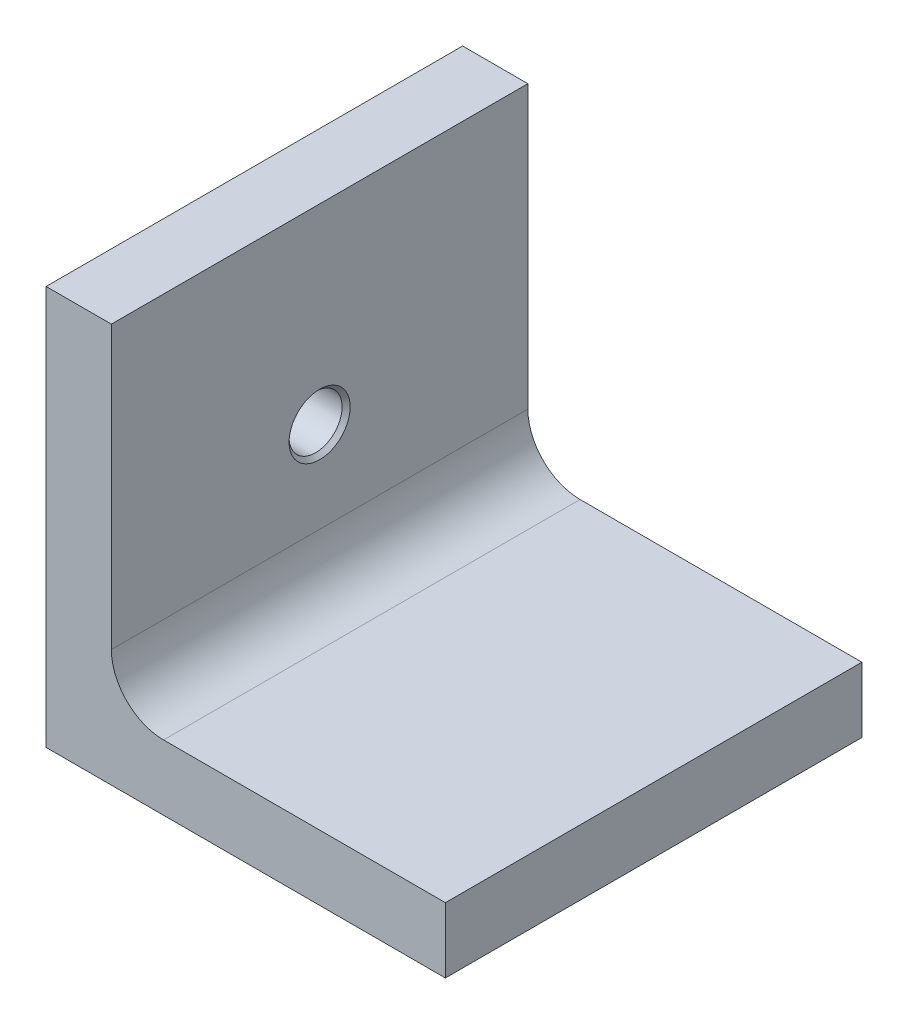
SolidWorks part; units mm, degrees
ref_plane "Front Plane" through (0, 0, 0) normal (0, 0, 1) x (1, 0, 0)
ref_plane "Top Plane" through (0, 0, 0) normal (0, 1, 0) x (1, 0, 0)
ref_plane "Right Plane" through (0, 0, 0) normal (1, 0, 0) x (0, 0, -1)
sketch "Sketch1" plane through (0, 0, 0) normal (0, 0, 1) x (1, 0, 0)
  line L0 (0, 36.5252) -> (0, 0)
  line L1 (0, 0) -> (36.5252, 0)
  line L2 (36.5252, 0) -> (36.5252, 5.969)
  line L3 (36.5252, 5.969) -> (10.7442, 5.969)
  line L4 (5.969, 10.7442) -> (5.969, 36.5252)
  line L5 (5.969, 36.5252) -> (0, 36.5252)
  arc A0 (10.7442, 5.969) -> (5.969, 10.7442) centre (10.7442, 10.7442) cw
  dimension "D5" = 4.7752
  dimension "D1" = 5.969
  dimension "D2" = 5.969
  dimension "D3" = 36.5252
  dimension "D4" = 36.5252
extrude "Boss-Extrude1" add sketch "Sketch1" along normal mid plane 38.1
hole_wizard "#11 (0.191) Diameter Hole1" positions "Sketch10" profile "Sketch9" hole size "#11" standard "Ansi Inch" end condition up to next
sketch "Sketch10" plane through (0, 0, 0) normal (-1, 0, 0) x (0, 0, 1)
  point P0 (0, 19.05)
  dimension "D1" = 19.05
sketch "Sketch9" plane through (0, 19.05, 0) normal (0, 1, 0) x (0, 0, 1)
  line L0 (0, 0) -> (0, 5.969)
  line L1 (0, 5.969) -> (2.794, 5.969)
  line L2 (2.4257, 5.6007) -> (2.4257, 0.3683)
  line L3 (2.4257, 0.3683) -> (2.794, 0)
  line L5 (2.794, 0) -> (0, 0)
  line L6 (-2.4257, 0.3683) -> (-2.794, 0) construction
  line L7 (2.794, 5.969) -> (2.4257, 5.6007)
  line L8 (-2.794, 5.969) -> (-2.4257, 5.6007) construction
  line L11 (0, -6.35) -> (0, 107.95) construction
  dimension "Thru Hole Dia." = 4.8514
  dimension "Thru Hole Depth" = 5.969
  dimension "Near C'Sink Dia." = 5.588
  dimension "Near C'Sink Angle" = 90
  dimension "Far C'Sink Dia." = 5.588
  dimension "Far C'Sink Angle" = 90
hole_wizard "#10-32 Tapped Hole1" positions "Sketch4" profile "Sketch3" tap size "#10-32" standard "Ansi Inch"
sketch "Sketch4" plane through (0, 0, 0) normal (-1, 0, 0) x (0, 0, 1)
  point P0 (0, 19.05)
  dimension "D1" = 19.05
sketch "Sketch3" plane through (0, 19.05, 0) normal (0, 1, 0) x (0, 0, 1)
  line L0 (0, 0) -> (0, 5.969)
  line L1 (0, 5.969) -> (2.667, 5.969)
  line L2 (2.0193, 5.3213) -> (2.0193, 0.6477)
  line L3 (2.0193, 0.6477) -> (2.667, 0)
  line L5 (2.667, 0) -> (0, 0)
  line L6 (-2.0193, 0.6477) -> (-2.667, 0) construction
  line L7 (2.667, 5.969) -> (2.0193, 5.3213)
  line L8 (-2.667, 5.969) -> (-2.0193, 5.3213) construction
  line L11 (0, -6.35) -> (0, 107.95) construction
  dimension "Thread Major Dia." = 4.0386
  dimension "Thru Tap Drill Depth" = 5.969
  dimension "Near C'Sink Dia." = 5.334
  dimension "Near C'Sink Angle" = 90
  dimension "Far C'Sink Dia." = 5.334
  dimension "Far C'Sink Angle" = 90
hole_wizard "#10-32 Tapped Hole2" positions "Sketch6" profile "Sketch5" tap size "#10-32" standard "Ansi Inch"
sketch "Sketch6" plane through (0, 0, 0) normal (0, -1, 0) x (1, 0, 0)
  point P0 (13.462, 0)
  dimension "D2" = 13.462
sketch "Sketch5" plane through (13.462, 0, 0) normal (1, 0, 0) x (0, 0, -1)
  line L0 (0, 0) -> (0, 5.969)
  line L1 (0, 5.969) -> (2.667, 5.969)
  line L2 (2.0193, 5.3213) -> (2.0193, 0.6477)
  line L3 (2.0193, 0.6477) -> (2.667, 0)
  line L5 (2.667, 0) -> (0, 0)
  line L6 (-2.0193, 0.6477) -> (-2.667, 0) construction
  line L7 (2.667, 5.969) -> (2.0193, 5.3213)
  line L8 (-2.667, 5.969) -> (-2.0193, 5.3213) construction
  line L11 (0, -6.35) -> (0, 107.95) construction
  dimension "Thread Major Dia." = 4.0386
  dimension "Thru Tap Drill Depth" = 5.969
  dimension "Near C'Sink Dia." = 5.334
  dimension "Near C'Sink Angle" = 90
  dimension "Far C'Sink Dia." = 5.334
  dimension "Far C'Sink Angle" = 90
hole_wizard "#8-32 Tapped Hole1" positions "Sketch8" profile "Sketch7" tap size "#8-32" standard "Ansi Inch"
sketch "Sketch8" plane through (0, 0, 0) normal (0, -1, 0) x (1, 0, 0)
  point P0 (23.8252, 3.175)
  dimension "D1" = 3.175
  dimension "D2" = 23.8252
sketch "Sketch7" plane through (23.8252, 0, 3.175) normal (1, 0, 0) x (0, 0, -1)
  line L0 (0, 0) -> (0, 5.969)
  line L1 (0, 5.969) -> (2.286, 5.969)
  line L2 (1.7272, 5.4102) -> (1.7272, 0.5588)
  line L3 (1.7272, 0.5588) -> (2.286, 0)
  line L5 (2.286, 0) -> (0, 0)
  line L6 (-1.7272, 0.5588) -> (-2.286, 0) construction
  line L7 (2.286, 5.969) -> (1.7272, 5.4102)
  line L8 (-2.286, 5.969) -> (-1.7272, 5.4102) construction
  line L11 (0, -6.35) -> (0, 107.95) construction
  dimension "Thread Major Dia." = 3.4544
  dimension "Thru Tap Drill Depth" = 5.969
  dimension "Near C'Sink Dia." = 4.572
  dimension "Near C'Sink Angle" = 90
  dimension "Far C'Sink Dia." = 4.572
  dimension "Far C'Sink Angle" = 90
